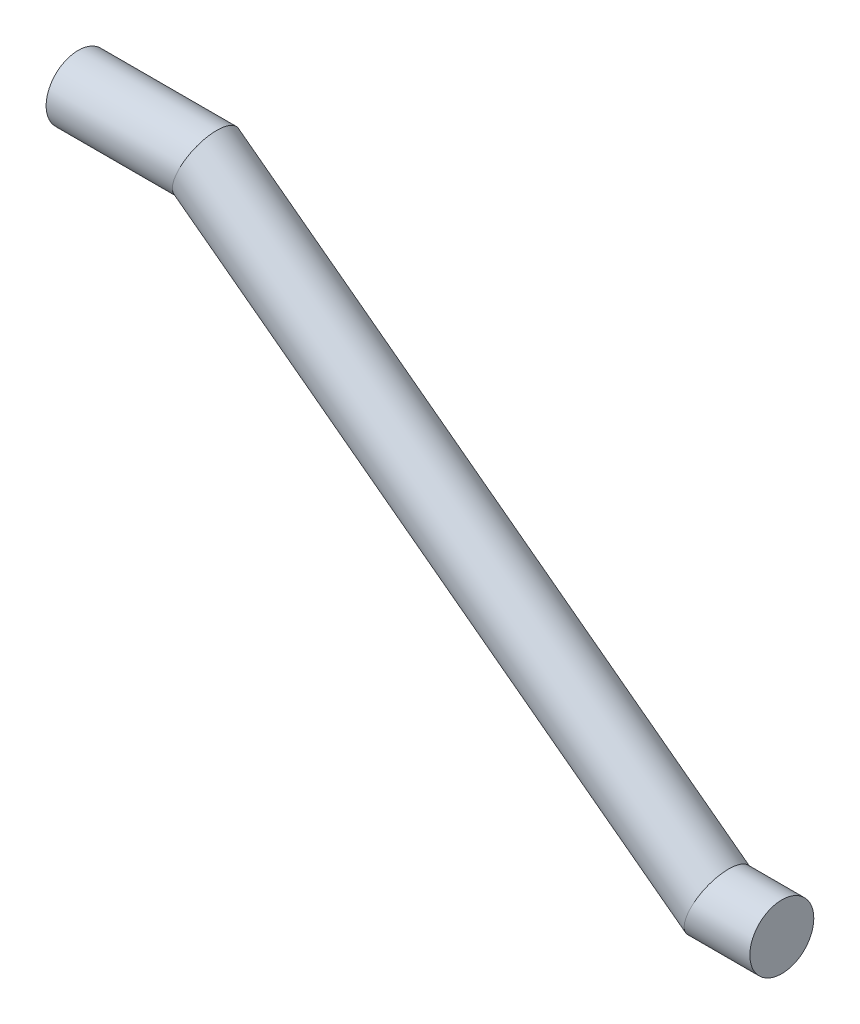
SolidWorks part; units mm, degrees
ref_plane "Front Plane" through (0, 0, 0) normal (0, 0, 1) x (1, 0, 0)
ref_plane "Top Plane" through (0, 0, 0) normal (0, 1, 0) x (1, 0, 0)
ref_plane "Right Plane" through (0, 0, 0) normal (1, 0, 0) x (0, 0, -1)
sketch "Sketch1" plane through (0, 0, 0) normal (1, 0, 0) x (0, 0, -1)
  circle A0 centre (0, 0) radius 25
  dimension "D1" = 50
sketch "Sketch2" plane through (0, 0, 0) normal (0, 0, 1) x (1, 0, 0)
  line L0 (0, 0) -> (100, 0)
  line L1 (0, -25) -> (0, 25) construction
  line L2 (100, 0) -> (500, -300)
  line L3 (500, -300) -> (550, -300)
  line L4 (100, 0) -> (100, -522.7742) construction
  line L5 (500, -300) -> (100, -300) construction
  dimension "D1" = 100
  dimension "D2" = 500
  dimension "D3" = 50
  dimension "D4" = 400
sweep "Sweep1" add profiles "Sketch1" path "Sketch2"
